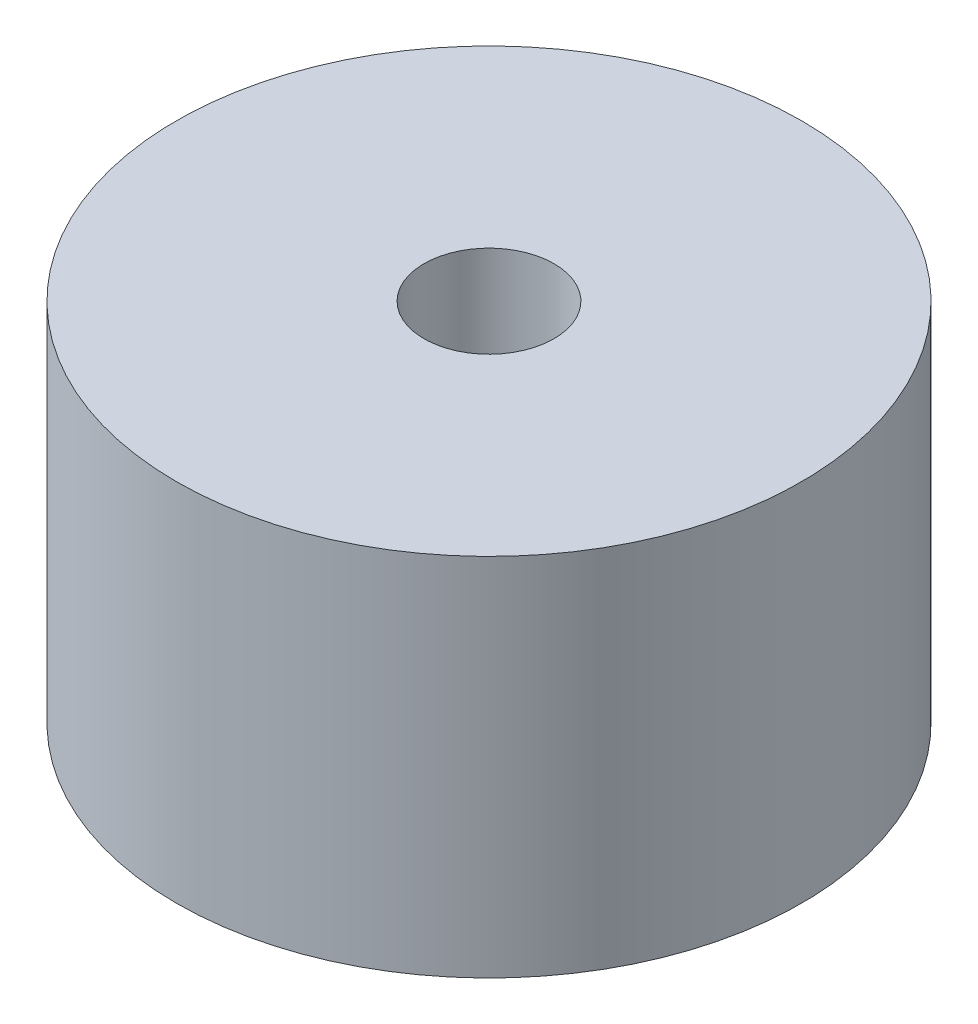
SolidWorks part; units mm, degrees
ref_plane "前视基准面" through (0, 0, 0) normal (0, 0, 1) x (1, 0, 0)
ref_plane "上视基准面" through (0, 0, 0) normal (0, 1, 0) x (1, 0, 0)
ref_plane "右视基准面" through (0, 0, 0) normal (1, 0, 0) x (0, 0, -1)
sketch "草图1" plane through (0, 0, 0) normal (0, 1, 0) x (1, 0, 0)
  circle A0 centre (0, 0) radius 12.5
  dimension "D1" = 25
extrude "凸台-拉伸1" add sketch "草图1" along normal blind 14.6
sketch "草图3" plane through (0, 0, 0) normal (0, -1, 0) x (1, 0, 0)
  circle A0 centre (0, 0) radius 2.6
  dimension "D1" = 5.2
extrude "切除-拉伸1" cut sketch "草图3" against normal through all
